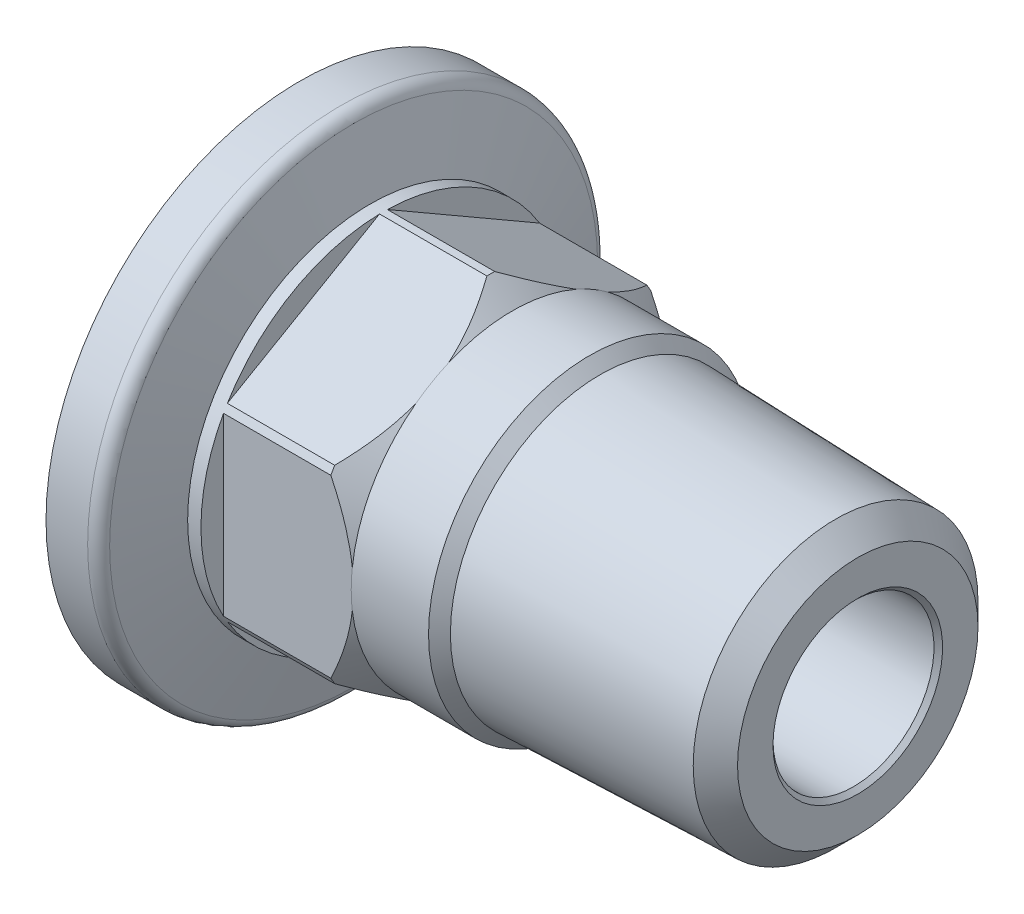
SolidWorks part; units mm, degrees
material "AISI 304"
ref_plane "Front Plane" through (0, 0, 0) normal (0, 0, 1) x (1, 0, 0)
ref_plane "Top Plane" through (0, 0, 0) normal (0, 1, 0) x (1, 0, 0)
ref_plane "Right Plane" through (0, 0, 0) normal (1, 0, 0) x (0, 0, -1)
sketch "Sketch1" plane through (0, 0, 0) normal (0, 0, 1) x (1, 0, 0)
  line L0 (0, 8.636) -> (0, 0) construction
  line L1 (2.4633, 14.9987) -> (0, 14.9987)
  line L2 (3.1993, 14.4339) -> (4.1744, 10.795)
  line L3 (0, 14.9987) -> (0, 8.636)
  line L4 (0, 8.636) -> (2.6162, 8.636)
  line L5 (2.6162, 8.636) -> (2.6162, 4.7625)
  line L6 (2.6162, 4.7625) -> (33.02, 4.7625)
  line L7 (17.78, 8.8582) -> (17.1537, 9.525)
  line L8 (0, 0) -> (29.2992, 0) construction
  line L10 (17.1537, 9.525) -> (12.5817, 9.525)
  line L11 (4.1744, 10.795) -> (11.3117, 10.795)
  line L12 (11.3117, 10.795) -> (12.5817, 9.525)
  line L13 (4.1744, 10.795) -> (4.1744, 8.0509) construction
  line L14 (17.78, 8.8582) -> (33.02, 8.382)
  line L15 (33.02, 8.382) -> (33.02, 4.7625)
  arc A0 (2.4633, 14.9987) -> (3.1993, 14.4339) centre (2.4633, 14.2367) cw
  point P15 (3.048, 14.9987)
  dimension "D2" = 9.525
  dimension "D7" = 0.762
  dimension "D1" = 29.9974
  dimension "D3" = 17.272
  dimension "D4" = 2.6162
  dimension "D5" = 3.048
  dimension "D6" = 135
  dimension "D8" = 21.59
  dimension "D9" = 105
  dimension "D10" = 1.79
  dimension "D11" = 45
  dimension "D12" = 19.05
  dimension "D13" = 16.764
  dimension "D14" = 15.24
  dimension "D15" = 4.572
  dimension "D16" = 33.02
revolve "Revolve1" add sketch "Sketch1" angle 360 about L8
cosmetic thread "Cosmetic Thread1" parameters "D2"=14.9352
sketch "Sketch9" plane through (33.02, 0, 0) normal (1, 0, 0) x (0, 0, -1)
  circle A0 centre (0, 0) radius 8.382 construction
  circle A1 centre (0, 0) radius 8.382
sketch "Sketch10" plane through (0, 0, 0) normal (0, 0, -1) x (1, 0, 0)
  line L0 (33.6876, -8.4029) -> (33.02, -7.2466)
  line L1 (33.02, -7.2466) -> (32.3524, -8.4029)
  line L2 (32.3524, -8.4029) -> (33.6876, -8.4029)
  line L4 (33.02, -8.382) -> (33.02, 8.382) construction
  line L5 (0, 0) -> (37.8021, 0) construction
  line L6 (0, 0) -> (29.2992, 0) construction
  line L7 (33.02, -7.2466) -> (33.02, -7.7724) construction
  line L10 (17.78, -8.8582) -> (33.02, -8.382) construction
  dimension "D1" = 60
  dimension "D2" = 0.5258
  dimension "D3" = 15.5448
chamfer "Chamfer2" distance 1.27 angle 45 1 edges at (33.02, 0, 8.382)
ref_plane "Plane1" through (12.5817, 0, 0) normal (1, 0, 0) x (0, 0, -1)
sketch "Sketch13" plane through (12.5817, 0, 0) normal (1, 0, 0) x (0, 0, -1)
  line L1 (0, 10.9252) -> (-9.4615, 5.4626)
  line L2 (-9.4615, 5.4626) -> (-9.4615, -5.4626)
  line L3 (-9.4615, -5.4626) -> (0, -10.9252)
  line L4 (0, -10.9252) -> (9.4615, -5.4626)
  line L5 (9.4615, -5.4626) -> (9.4615, 5.4626)
  line L6 (9.4615, 5.4626) -> (0, 10.9252)
  circle A0 centre (0, 0) radius 9.4615 construction
  dimension "D1" = 18.923
extrude "Cut-Extrude3" cut sketch "Sketch13" against normal blind 7.62 flip side to cut
chamfer "Chamfer3" distance 0.254 angle 45 1 edges at (33.02, 0, 4.7625)
